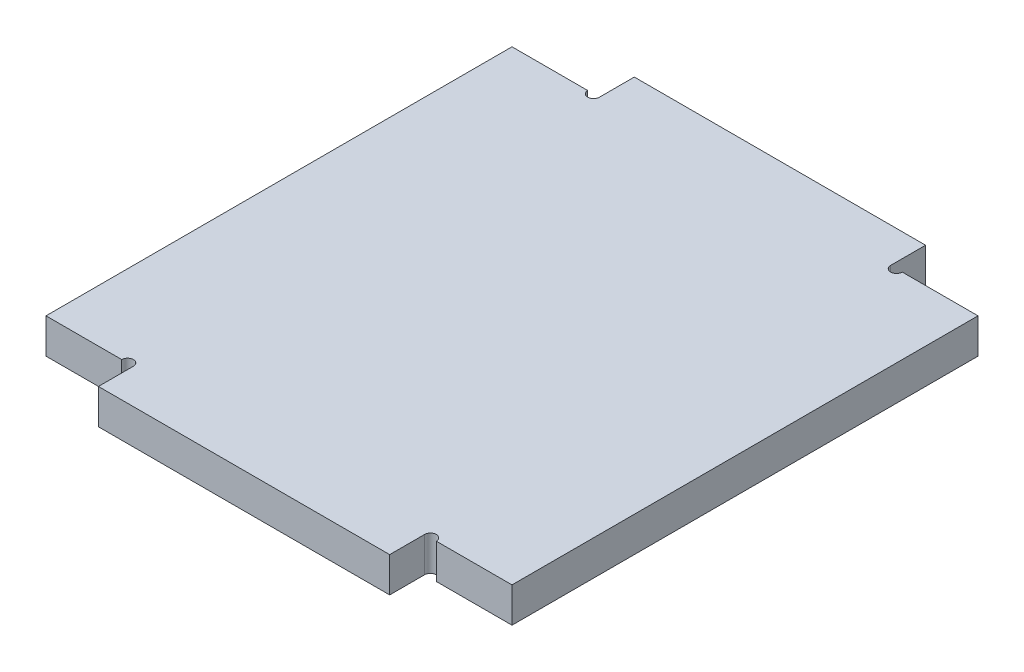
SolidWorks part; units mm, degrees
ref_plane "Front Plane" through (0, 0, 0) normal (0, 0, 1) x (1, 0, 0)
ref_plane "Top Plane" through (0, 0, 0) normal (0, 1, 0) x (1, 0, 0)
ref_plane "Right Plane" through (0, 0, 0) normal (1, 0, 0) x (0, 0, -1)
sketch "Sketch1" plane through (0, 0, 0) normal (0, 1, 0) x (1, 0, 0)
  line L0 (0, 20) -> (40, 20) construction
  line L1 (0, 0) -> (6.5, 0)
  line L2 (0, 0) -> (0, 40)
  line L3 (0, 40) -> (6.5, 40)
  line L4 (40, 0) -> (40, 40)
  line L5 (33.5, 40) -> (40, 40)
  line L7 (7.5, 40) -> (7.5, 43)
  line L8 (7.5, 43) -> (32.5, 43)
  line L9 (32.5, 40) -> (32.5, 43)
  line L10 (32.5, 0) -> (32.5, -3)
  line L11 (7.5, 0) -> (7.5, -3)
  line L12 (7.5, -3) -> (32.5, -3)
  line L13 (33.5, 0) -> (40, 0)
  arc A0 (6.5, 40) -> (7.5, 40) centre (7, 40) ccw
  arc A1 (32.5, 40) -> (33.5, 40) centre (33, 40) ccw
  arc A2 (32.5, 0) -> (33.5, 0) centre (33, 0) cw
  arc A3 (6.5, 0) -> (7.5, 0) centre (7, 0) cw
  point P11 (20, 43)
  point P12 (20, 20)
  dimension "D5" = 0.5
  dimension "D1" = 40
  dimension "D2" = 3
  dimension "D3" = 25
  dimension "D4" = 40
extrude "Boss-Extrude1" add sketch "Sketch1" along normal blind 3
